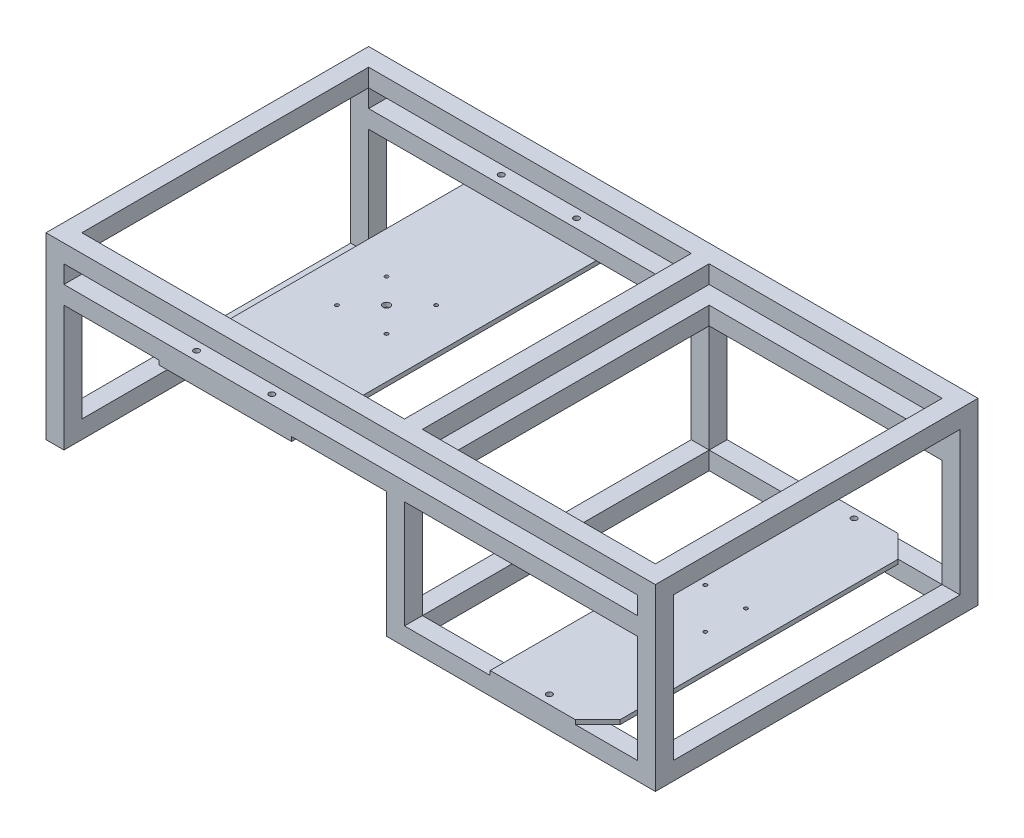
SolidWorks part; units mm, degrees
ref_plane "Front Plane" through (0, 0, 0) normal (0, 0, 1) x (1, 0, 0)
ref_plane "Top Plane" through (0, 0, 0) normal (0, 1, 0) x (1, 0, 0)
ref_plane "Right Plane" through (0, 0, 0) normal (1, 0, 0) x (0, 0, -1)
sketch "Sketch1" plane through (0, 0, 0) normal (0, 1, 0) x (1, 0, 0)
  line L0 (0, 376.3012) -> (0, -520.3513) construction
  line L1 (-425, 225) -> (425, 225) construction
  line L2 (-425, 225) -> (-425, -225) construction
  line L3 (-425, -225) -> (425, -225) construction
  line L4 (425, 225) -> (425, -225) construction
  line L5 (-425, 225) -> (-400, 225)
  line L6 (-425, 225) -> (-425, -225)
  line L7 (-425, -225) -> (-400, -225)
  line L8 (-400, 225) -> (-400, -225)
  line L9 (425, -225) -> (400, -225)
  line L10 (400, 225) -> (400, -225)
  line L11 (425, 225) -> (400, 225)
  line L12 (425, 225) -> (425, -225)
  point P0 (0, 0)
  dimension "D1" = 850
  dimension "D2" = 450
  dimension "D3" = 25
extrude "Boss-Extrude2" add sketch "Sketch1" along normal blind 25
sketch "Sketch2" plane through (0, 25, 0) normal (0, 1, 0) x (1, 0, 0)
  line L0 (-400, -225) -> (-400, 225) construction
  line L1 (-425, 225) -> (-400, 225)
  line L2 (-425, 225) -> (-425, 200)
  line L3 (-425, 200) -> (-400, 200)
  line L4 (-400, 225) -> (-400, 200)
  line L6 (-425, -225) -> (-400, -225)
  line L7 (-425, -225) -> (-425, -200)
  line L8 (-425, -200) -> (-400, -200)
  line L9 (-400, -225) -> (-400, -200)
  dimension "D1" = 25
  dimension "D2" = 25
extrude "Boss-Extrude3" add sketch "Sketch2" along normal blind 200
sketch "Sketch3" plane through (0, 225, 0) normal (0, 1, 0) x (1, 0, 0)
  line L1 (-425, 225) -> (-400, 225)
  line L2 (-425, 225) -> (-425, -225)
  line L3 (-425, -225) -> (-400, -225)
  line L4 (-400, 225) -> (-400, -225)
extrude "Boss-Extrude4" add sketch "Sketch3" along normal blind 25
sketch "Sketch4" plane through (-400, 0, 0) normal (1, 0, 0) x (0, 0, -1)
  line L0 (-200, 225) -> (200, 225) construction
  line L1 (225, 250) -> (200, 250) construction
  line L2 (225, 250) -> (225, 225) construction
  line L3 (225, 225) -> (200, 225) construction
  line L4 (200, 250) -> (200, 225) construction
  line L6 (-225, 250) -> (-200, 250) construction
  line L7 (-225, 250) -> (-225, 225) construction
  line L8 (-225, 225) -> (-200, 225) construction
  line L9 (-200, 250) -> (-200, 225) construction
sketch "Sketch5" plane through (0, 25, 0) normal (0, 1, 0) x (1, 0, 0)
  line L0 (425, -225) -> (425, 225) construction
  line L1 (400, 225) -> (425, 225)
  line L2 (400, 225) -> (400, 200)
  line L3 (400, 200) -> (425, 200)
  line L4 (425, 225) -> (425, 200)
  line L6 (400, -225) -> (425, -225)
  line L7 (400, -225) -> (400, -200)
  line L8 (400, -200) -> (425, -200)
  line L9 (425, -225) -> (425, -200)
  dimension "D1" = 25
  dimension "D2" = 25
extrude "Boss-Extrude5" add sketch "Sketch5" along normal blind 200
sketch "Sketch6" plane through (0, 225, 0) normal (0, 1, 0) x (1, 0, 0)
  line L1 (400, 225) -> (425, 225)
  line L2 (400, 225) -> (400, -225)
  line L3 (400, -225) -> (425, -225)
  line L4 (425, 225) -> (425, -225)
extrude "Boss-Extrude6" add sketch "Sketch6" along normal blind 25
ref_plane "Plane1" through (0, 250, 0) normal (0, 1, 0) x (1, 0, 0)
sketch "Sketch7" plane through (0, 250, 0) normal (0, 1, 0) x (1, 0, 0)
  line L1 (400, 225) -> (-400, 225)
  line L2 (400, 225) -> (400, 200)
  line L3 (400, 200) -> (-400, 200)
  line L4 (-400, 225) -> (-400, 200)
  line L5 (400, -225) -> (-400, -225)
  line L6 (400, -225) -> (400, -200)
  line L7 (400, -200) -> (-400, -200)
  line L8 (-400, -225) -> (-400, -200)
extrude "Boss-Extrude7" add sketch "Sketch7" against normal blind 25
ref_plane "Plane2" through (0, 0, 0) normal (0, -1, 0) x (-1, 0, 0)
sketch "Sketch8" plane through (0, 0, 0) normal (0, -1, 0) x (-1, 0, 0)
  line L1 (-400, 225) -> (-50, 225)
  line L2 (-400, 225) -> (-400, 200)
  line L3 (-400, 200) -> (-50, 200)
  line L4 (-50, 225) -> (-50, 200)
  line L9 (400, -225) -> (-400, -225) construction
  line L10 (-400, -200) -> (-50, -200)
  line L11 (-400, -200) -> (-400, -225)
  line L12 (-400, -225) -> (-50, -225)
  line L13 (-50, -200) -> (-50, -225)
  dimension "D1" = 350
  dimension "D4" = 25
extrude "Boss-Extrude8" add sketch "Sketch8" against normal blind 25
sketch "Sketch9" plane through (0, 0, 0) normal (0, -1, 0) x (-1, 0, 0)
  line L0 (-50, -225) -> (-425, -225) construction
  line L1 (-50, 200) -> (-75, 200)
  line L2 (-50, 200) -> (-50, -225)
  line L3 (-50, -225) -> (-75, -225)
  line L4 (-75, 200) -> (-75, -225)
  dimension "D1" = 25
extrude "Boss-Extrude9" add sketch "Sketch9" against normal blind 25
sketch "Sketch10" plane through (400, 0, 0) normal (-1, 0, 0) x (0, 0, 1)
  line L0 (200, 225) -> (200, 25) construction
  line L1 (200, 200) -> (225, 200)
  line L2 (200, 200) -> (200, 175)
  line L3 (200, 175) -> (225, 175)
  line L4 (225, 200) -> (225, 175)
  line L5 (225, 250) -> (225, 0) construction
  line L6 (225, 225) -> (200, 225) construction
  line L7 (0, 165.7702) -> (0, -166.8325) construction
  line L8 (-200, 175) -> (-225, 175)
  line L9 (-225, 200) -> (-225, 175)
  line L10 (-200, 200) -> (-225, 200)
  line L11 (-200, 200) -> (-200, 175)
  dimension "D1" = 25
  dimension "D2" = 25
extrude "Boss-Extrude10" add sketch "Sketch10" along normal blind 800
sketch "Sketch14" plane through (0, 25, 0) normal (0, 1, 0) x (1, 0, 0)
  line L1 (50, 225) -> (75, 225)
  line L2 (50, 225) -> (50, 200)
  line L3 (50, 200) -> (75, 200)
  line L4 (75, 225) -> (75, 200)
  line L5 (50, -225) -> (75, -225)
  line L6 (50, -225) -> (50, -200)
  line L7 (50, -200) -> (75, -200)
  line L8 (75, -225) -> (75, -200)
extrude "Boss-Extrude13" add sketch "Sketch14" along normal up to next
sketch "Sketch15" plane through (0, 175, 0) normal (0, -1, 0) x (1, 0, 0)
  line L0 (-400, 225) -> (50, 225) construction
  line L1 (-400, 225) -> (-400, 200) construction
  line L2 (-267.5, 225) -> (-82.5, 225)
  line L3 (-267.5, 225) -> (-267.5, -225)
  line L4 (-267.5, -225) -> (-82.5, -225)
  line L5 (-82.5, 225) -> (-82.5, -225)
  line L6 (-400, -225) -> (50, -225) construction
  dimension "D1" = 185
  dimension "D2" = 132.5
extrude "Boss-Extrude14" add sketch "Sketch15" along normal blind 6
sketch "Sketch18" plane through (0, 25, 0) normal (0, 1, 0) x (1, 0, 0)
  line L0 (75, 225) -> (400, 225) construction
  line L1 (194.6028, 225) -> (313.2542, 225)
  line L2 (194.6028, 225) -> (194.6028, -225)
  line L3 (194.6028, -225) -> (313.2542, -225)
  line L4 (344.6028, 193.6514) -> (344.6028, -193.6514)
  line L6 (313.2542, 225) -> (344.6028, 193.6514)
  line L8 (313.2542, -225) -> (344.6028, -193.6514)
  dimension "D1" = 150
extrude "Boss-Extrude15" add sketch "Sketch18" along normal blind 6
sketch "Sketch19" plane through (0, 169, 0) normal (0, -1, 0) x (1, 0, 0)
  line L0 (-267.5, 225) -> (-267.5, -225) construction
  line L1 (-82.5, 200) -> (-82.5, 225) construction
  line L2 (-606.3881, 0) -> (499.8837, 0) construction
  circle A0 centre (-227.5, 212.5) radius 4
  circle A1 centre (-122.5, 212.5) radius 4
  circle A2 centre (-227.5, -212.5) radius 4
  circle A3 centre (-122.5, -212.5) radius 4
  point P11 (-122.5, -212.5)
  dimension "D3" = 8
  dimension "D4" = 8
  dimension "D1" = 40
  dimension "D2" = 40
extrude "Cut-Extrude2" cut sketch "Sketch19" against normal up to next
sketch "Sketch20" plane through (0, 31, 0) normal (0, 1, 0) x (1, 0, 0)
  line L0 (313.2542, 225) -> (194.6028, 225) construction
  line L1 (194.6028, 225) -> (194.6028, -225) construction
  line L2 (-569.9909, 0) -> (604.7605, 0) construction
  circle A0 centre (264.6028, 212.5) radius 4
  circle A1 centre (264.6028, -212.5) radius 4
  dimension "D3" = 8
  dimension "D1" = 12.5
  dimension "D2" = 70
extrude "Cut-Extrude4" cut sketch "Sketch20" against normal up to next
sketch "Sketch21" plane through (0, 169, 0) normal (0, -1, 0) x (1, 0, 0)
  line L0 (-175, 0) -> (-214.9994, 39.9994) construction
  circle A0 centre (-175, 0) radius 5
  circle A1 centre (-209.6267, 34.6267) radius 2.5
  circle A2 centre (-140.3733, 34.6267) radius 2.5
  circle A3 centre (-140.3733, -34.6267) radius 2.5
  circle A4 centre (-209.6267, -34.6267) radius 2.5
  point P14 (-175, 0)
  dimension "D1" = 10
  dimension "D4" = 5
  dimension "D2" = 48.9695
  dimension "D3" = 4
extrude "Cut-Extrude5" cut sketch "Sketch21" against normal blind 10
sketch "Sketch24" plane through (0, 0, -200) normal (0, 0, 1) x (1, 0, 0)
  line L0 (-400, 200) -> (400, 200) construction
  line L1 (50, 175) -> (75, 175)
  line L2 (50, 175) -> (50, 200)
  line L3 (50, 200) -> (75, 200)
  line L4 (75, 175) -> (75, 200)
  line L5 (-400, 225) -> (400, 225) construction
  line L6 (75, 225) -> (50, 225)
  line L7 (75, 225) -> (75, 250)
  line L8 (75, 250) -> (50, 250)
  line L9 (50, 225) -> (50, 250)
  line L10 (-400, 250) -> (400, 250) construction
extrude "Boss-Extrude16" add sketch "Sketch24" along normal up to next
sketch "Sketch25" plane through (0, 31, 0) normal (0, 1, 0) x (1, 0, 0)
  line L3 (269.6028, 0) -> (177.6618, 91.941) construction
  circle A1 centre (241.3185, 28.2843) radius 2.5
  circle A2 centre (297.8871, 28.2843) radius 2.5
  circle A3 centre (297.8871, -28.2843) radius 2.5
  circle A4 centre (241.3185, -28.2843) radius 2.5
  point P20 (269.6028, 0)
  dimension "D2" = 5
  dimension "D1" = 40
  dimension "D4" = 4
extrude "Cut-Extrude6" cut sketch "Sketch25" against normal blind 10
